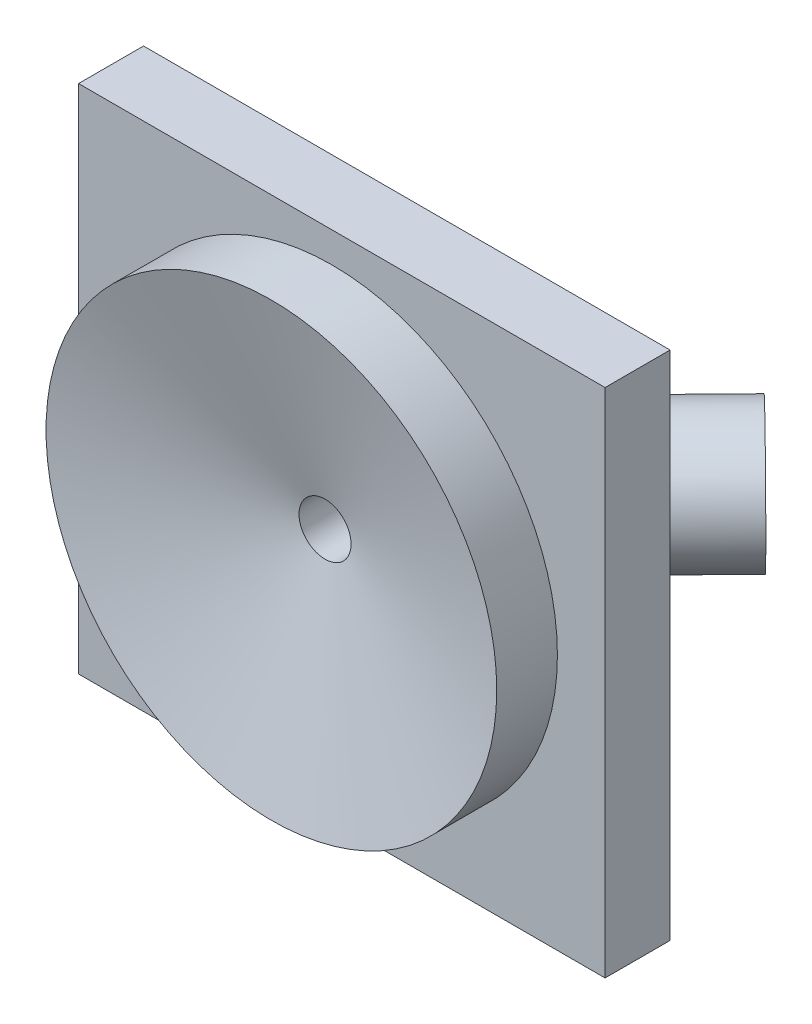
SolidWorks part; units mm, degrees
ref_plane "Front Plane" through (0, 0, 0) normal (0, 0, 1) x (1, 0, 0)
ref_plane "Top Plane" through (0, 0, 0) normal (0, 1, 0) x (1, 0, 0)
ref_plane "Right Plane" through (0, 0, 0) normal (1, 0, 0) x (0, 0, -1)
sketch "Sketch1" plane through (0, 0, 0) normal (0, 1, 0) x (1, 0, 0)
  line L4 (27.3128, 4.648) -> (32.5128, 4.648)
  line L7 (27.3128, 3.148) -> (27.3128, 4.648)
  line L8 (32.5128, 4.648) -> (32.5128, 1.748)
  line L10 (27.3128, 3.148) -> (32.5128, 1.748)
  dimension "D1" = 5.2
  dimension "D2" = 2.9
  dimension "D3" = 1.5
revolve "Revolve1" add sketch "Sketch1" angle 360 about L7
sketch "Sketch5" plane through (0, 0, 0) normal (0, 0, 1) x (1, 0, 0)
  circle A0 centre (27.3128, 0) radius 0.6
sketch "Sketch7" plane through (0, 0, -4.648) normal (0, 0, -1) x (-1, 0, 0)
  circle A0 centre (-27.3128, 0) radius 1.475
  circle A1 centre (-27.3128, 0) radius 5.2 construction
  dimension "D1" = 3.725
sketch "Sketch8" plane through (0, 0, 0) normal (0, 1, 0) x (1, 0, 0)
  line L0 (27.4128, 4.648) -> (31.5554, 8.8907)
  line L1 (27.4128, 4.648) -> (27.4128, 3.648)
  line L3 (32.5128, 1.748) -> (32.5128, 4.648) construction
  dimension "D1" = 5.1
sweep "Sweep2" add profiles "Sketch7" path "Sketch8"
sketch "Sketch10" plane through (0, 0, -4.648) normal (0, 0, -1) x (-1, 0, 0)
  line L0 (-33.6128, -5.9) -> (-21.4628, -5.9)
  line L2 (-21.4628, -5.9) -> (-21.4628, 5.9)
  line L3 (-21.4628, 5.9) -> (-33.6128, 5.9)
  line L4 (-33.6128, 5.9) -> (-33.6128, -5.9)
  circle A1 centre (-27.3128, 0) radius 5.2 construction
  dimension "D1" = 5.9
  dimension "D2" = 5.9
  dimension "D3" = 5.85
  dimension "D4" = 6.3
extrude "Boss-Extrude1" add sketch "Sketch10" against normal blind 1.5
sketch "Sketch9" plane through (0, 0, 0) normal (0, 1, 0) x (1, 0, 0)
  line L0 (27.4128, 0) -> (27.4128, 4.648)
  line L2 (27.4128, 4.648) -> (31.6554, 8.8907)
  dimension "D1" = 6
  dimension "D2" = 135
sweep "Cut-Sweep2" cut profiles "Sketch5" path "Sketch9"
